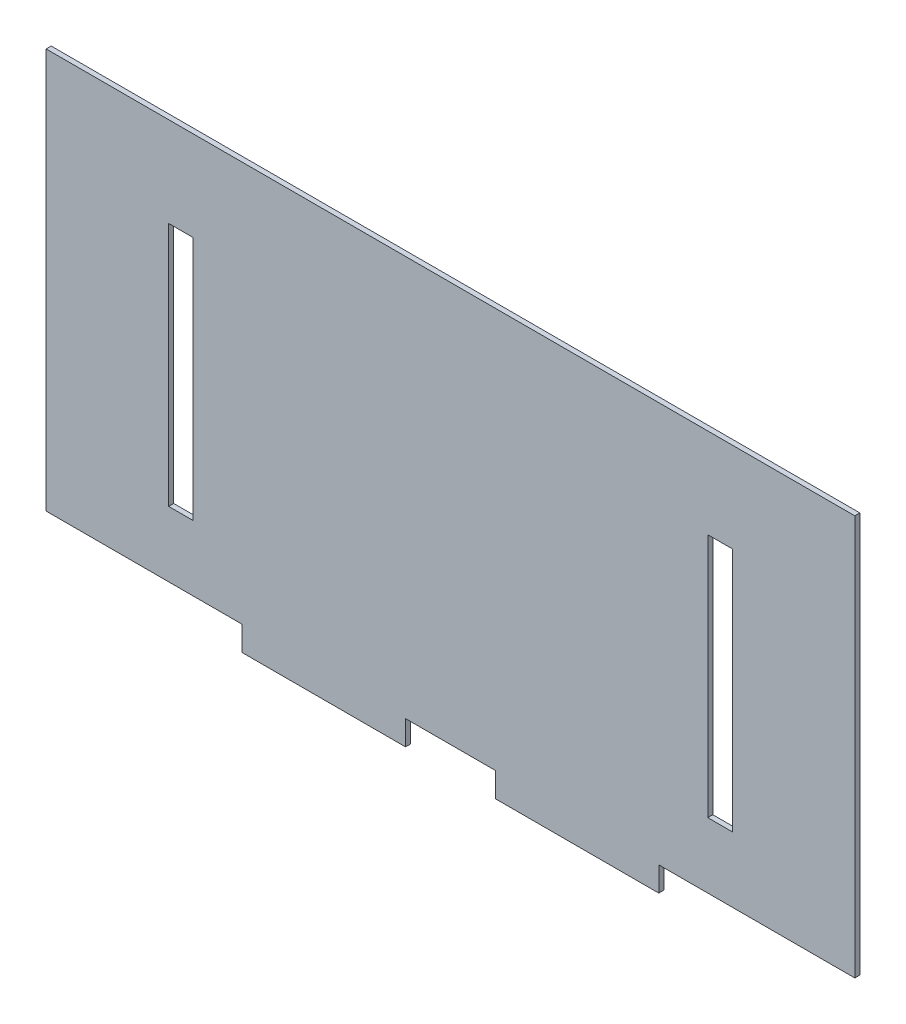
SolidWorks part; units mm, degrees
ref_plane "Front Plane" through (0, 0, 0) normal (0, 0, 1) x (1, 0, 0)
ref_plane "Top Plane" through (0, 0, 0) normal (0, 1, 0) x (1, 0, 0)
ref_plane "Right Plane" through (0, 0, 0) normal (1, 0, 0) x (0, 0, -1)
sketch "Sketch1" plane through (0, 0, 0) normal (0, 0, 1) x (1, 0, 0)
  line L1692 (489.7222, 1088.6693) -> (373.5598, 1088.6693)
  line L1693 (373.5598, 1088.6693) -> (373.5598, 1074.1494)
  line L1694 (373.5598, 1074.1494) -> (276.7595, 1074.1494)
  line L1695 (276.7595, 1074.1494) -> (276.7595, 1088.6693)
  line L1696 (276.7595, 1088.6693) -> (223.5222, 1088.6693)
  line L1697 (223.5222, 1088.6693) -> (223.5222, 1074.1494)
  line L1698 (223.5222, 1074.1494) -> (126.7219, 1074.1494)
  line L1699 (126.7219, 1074.1494) -> (126.7219, 1088.6693)
  line L1700 (126.7219, 1088.6693) -> (10.5629, 1088.6693)
  line L1701 (10.5629, 1088.6693) -> (10.5629, 1325.8195)
  line L1702 (10.5629, 1325.8195) -> (489.7222, 1325.8195)
  line L1703 (489.7222, 1325.8195) -> (489.7222, 1088.6693)
  line L1704 (402.5979, 1272.5805) -> (417.1228, 1272.5805)
  line L1705 (417.1228, 1272.5805) -> (417.1228, 1127.3817)
  line L1706 (417.1228, 1127.3817) -> (402.5979, 1127.3817)
  line L1707 (402.5979, 1127.3817) -> (402.5979, 1272.5805)
  line L1708 (83.1606, 1272.5805) -> (97.6838, 1272.5805)
  line L1709 (97.6838, 1272.5805) -> (97.6838, 1127.3817)
  line L1710 (97.6838, 1127.3817) -> (83.1606, 1127.3817)
  line L1711 (83.1606, 1127.3817) -> (83.1606, 1272.5805)
extrude "Boss-Extrude1" add sketch "Sketch1" along normal blind 3
